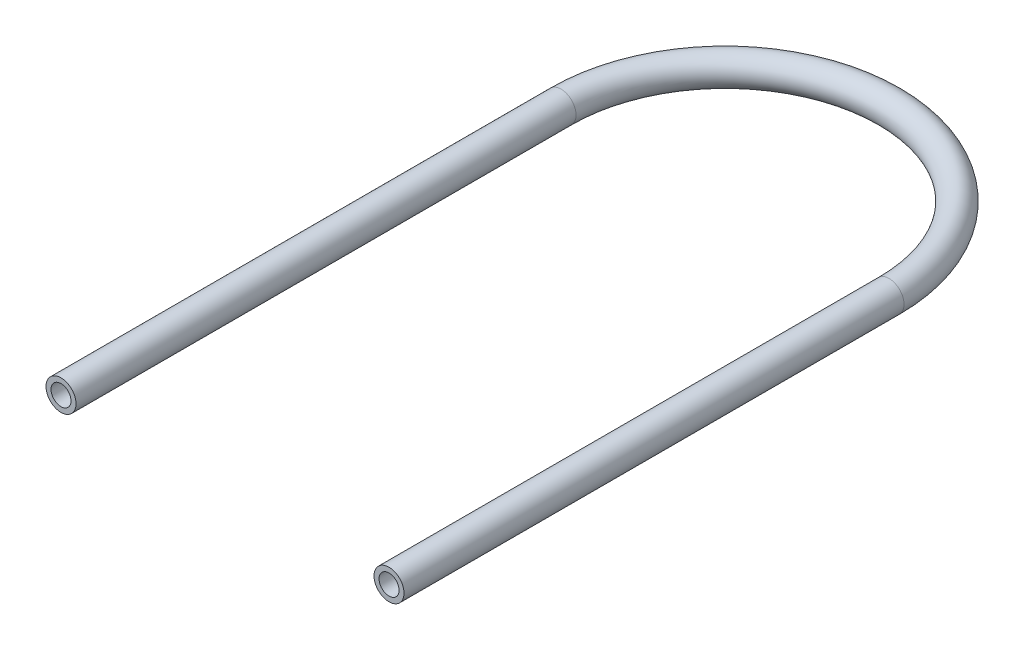
SolidWorks part; units mm, degrees
ref_plane "Front Plane" through (0, 0, 0) normal (0, 0, 1) x (1, 0, 0)
ref_plane "Top Plane" through (0, 0, 0) normal (0, 1, 0) x (1, 0, 0)
ref_plane "Right Plane" through (0, 0, 0) normal (1, 0, 0) x (0, 0, -1)
sketch "Sketch1" plane through (0, 0, 0) normal (0, 1, 0) x (1, 0, 0)
  line L0 (-41.7882, -18.2353) -> (-41.7882, 31.7647)
  line L1 (-8.9882, 31.7647) -> (-8.9882, -18.2353)
  arc A0 (-41.7882, 31.7647) -> (-8.9882, 31.7647) centre (-25.3882, 31.7647) cw
  dimension "D1" = 16.4
  dimension "D2" = 50
  dimension "D3" = 50
ref_plane "Plane1" through (-41.7882, 0, 18.2353) normal (0, 0, -1) x (-1, 0, 0)
sketch "Sketch2" plane through (-41.7882, 0, 18.2353) normal (0, 0, -1) x (-1, 0, 0)
  line L0 (0, 0) -> (-32.8, 0) construction
  circle A0 centre (0, 0) radius 1.5
  circle A1 centre (0, 0) radius 1
  dimension "D1" = 3
  dimension "D2" = 0.5
sweep "Sweep1" add profiles "Sketch2" path "Sketch1"
